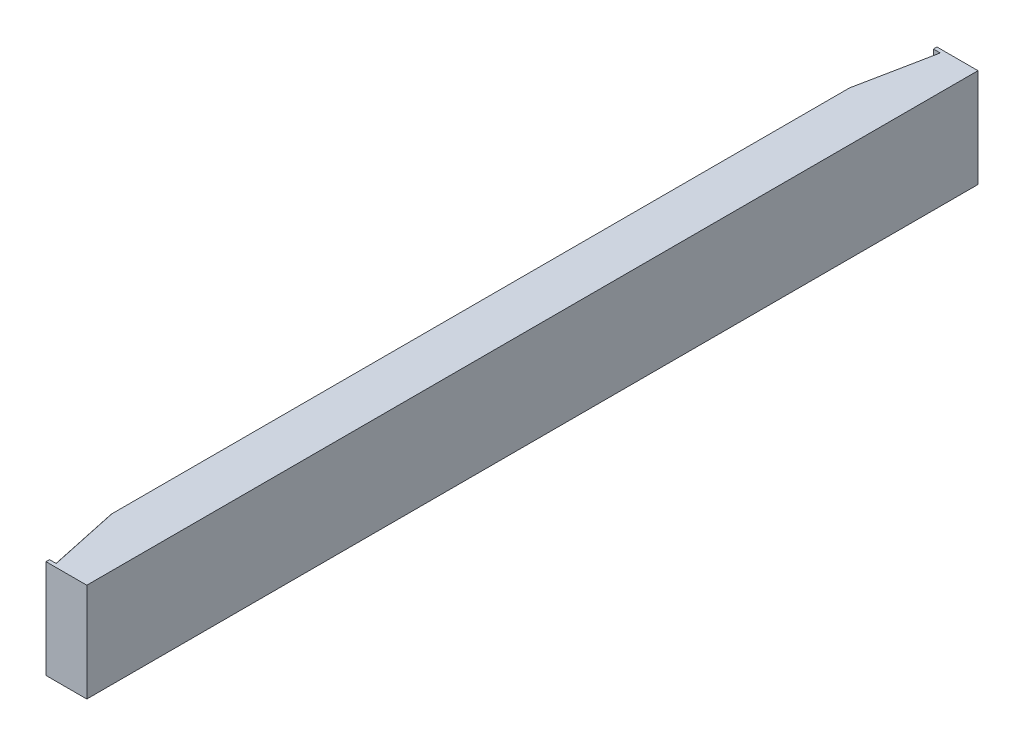
SolidWorks part; units mm, degrees
ref_plane "Front Plane" through (0, 0, 0) normal (0, 0, 1) x (1, 0, 0)
ref_plane "Top Plane" through (0, 0, 0) normal (0, 1, 0) x (1, 0, 0)
ref_plane "Right Plane" through (0, 0, 0) normal (1, 0, 0) x (0, 0, -1)
sketch "Sketch1" plane through (0, 0, 0) normal (0, 0, 1) x (1, 0, 0)
  line L1 (300, 147.1759) -> (450, 147.1759)
  line L2 (300, 147.1759) -> (300, -152.8241)
  line L3 (300, -152.8241) -> (450, -152.8241)
  line L4 (450, 147.1759) -> (450, -152.8241)
  line L5 (0, 0) -> (300, -2.8241) construction
  line L14 (0, 275) -> (0, -275)
  line L15 (0, -275) -> (300, -275)
  line L16 (300, -275) -> (300, 275)
  line L17 (300, 275) -> (0, 275)
  dimension "D2" = 300
  dimension "D3" = 150
extrude "Boss-Extrude1" add sketch "Sketch1" along normal blind 500 and the other way blind 1600 contours L4 L1 L2 L16 L3
sketch "Sketch2" plane through (0, 0, -1600) normal (0, 0, -1) x (-1, 0, 0)
  line L22 (-300, 49.6759) -> (-300, 69.6759)
  line L23 (-300, 69.6759) -> (-325, 69.6759)
  line L24 (-325, 69.6759) -> (-325, 77.1759)
  line L25 (-300, 129.6759) -> (-325, 129.6759)
  line L26 (-300, 147.1759) -> (-300, -152.8241) construction
  line L27 (-325, 129.6759) -> (-325, 137.1759)
  line L28 (-325, 137.1759) -> (-345, 137.1759)
  line L29 (-345, 137.1759) -> (-345, 102.1759)
  line L30 (-345, 102.1759) -> (-325, 102.1759)
  line L31 (-325, 102.1759) -> (-325, 109.6759)
  line L32 (-325, 109.6759) -> (-300, 109.6759)
  line L33 (-300, 109.6759) -> (-300, 129.6759)
  line L66 (-300, 147.1759) -> (-450, 147.1759) construction
  line L67 (-300, 119.6759) -> (-390, 119.6759) construction
  line L68 (-325, 77.1759) -> (-345, 77.1759)
  line L69 (-345, 77.1759) -> (-345, 42.1759)
  line L70 (-345, 42.1759) -> (-325, 42.1759)
  line L71 (-325, 42.1759) -> (-325, 49.6759)
  line L72 (-325, 49.6759) -> (-300, 49.6759)
  line L73 (-300, -10.3241) -> (-300, 9.6759)
  line L74 (-300, 9.6759) -> (-325, 9.6759)
  line L75 (-325, 9.6759) -> (-325, 17.1759)
  line L76 (-325, 17.1759) -> (-345, 17.1759)
  line L77 (-345, 17.1759) -> (-345, -17.8241)
  line L78 (-345, -17.8241) -> (-325, -17.8241)
  line L79 (-325, -17.8241) -> (-325, -10.3241)
  line L80 (-325, -10.3241) -> (-300, -10.3241)
  line L81 (-300, -70.3241) -> (-300, -50.3241)
  line L82 (-300, -50.3241) -> (-325, -50.3241)
  line L83 (-325, -50.3241) -> (-325, -42.8241)
  line L84 (-325, -42.8241) -> (-345, -42.8241)
  line L85 (-345, -42.8241) -> (-345, -77.8241)
  line L86 (-345, -77.8241) -> (-325, -77.8241)
  line L87 (-325, -77.8241) -> (-325, -70.3241)
  line L88 (-325, -70.3241) -> (-300, -70.3241)
  line L89 (-300, -130.3241) -> (-300, -110.3241)
  line L90 (-300, -110.3241) -> (-325, -110.3241)
  line L91 (-325, -110.3241) -> (-325, -102.8241)
  line L92 (-325, -102.8241) -> (-345, -102.8241)
  line L93 (-345, -102.8241) -> (-345, -137.8241)
  line L94 (-345, -137.8241) -> (-325, -137.8241)
  line L95 (-325, -137.8241) -> (-325, -130.3241)
  line L96 (-325, -130.3241) -> (-300, -130.3241)
  point P52 (-345, 119.6759)
  dimension "D1" = 5
  dimension "D2" = 20
  dimension "D4" = 45
  dimension "D5" = 25
  dimension "D3" = 10
  dimension "D6" = 20
  dimension "D7" = 35
extrude "Cut-Extrude1" cut sketch "Sketch2" against normal blind 2309
sketch "Sketch5" plane through (0, 0, 500) normal (0, 0, 1) x (1, 0, 0)
  line L1 (300, -152.8241) -> (450, -152.8241)
  line L2 (300, -152.8241) -> (300, 147.1759)
  line L3 (300, 147.1759) -> (450, 147.1759)
  line L4 (450, -152.8241) -> (450, 147.1759)
extrude "Boss-Extrude2" add sketch "Sketch5" along normal blind 350
sketch "Sketch6" plane through (300, 0, 0) normal (-1, 0, 0) x (0, 0, 1)
  line L0 (850, 147.1759) -> (850, -152.8241) construction
  line L1 (580, -127.8241) -> (790, -127.8241)
  line L2 (580, -127.8241) -> (580, 122.1759)
  line L3 (580, 122.1759) -> (790, 122.1759)
  line L4 (790, -127.8241) -> (790, 122.1759)
  line L6 (-1600, -152.8241) -> (850, -152.8241) construction
  line L7 (-1600, 147.1759) -> (850, 147.1759) construction
  dimension "D1" = 60
  dimension "D3" = 25
  dimension "D4" = 25
extrude "Cut-Extrude4" cut sketch "Sketch6" against normal blind 45
sketch "Sketch7" plane through (0, 122.1759, 0) normal (0, -1, 0) x (1, 0, 0)
  line L0 (300, 580) -> (345, 790)
  line L1 (345, 790) -> (300, 790)
  line L2 (300, 790) -> (300, 580)
extrude "Cut-Extrude5" cut sketch "Sketch7" against normal mid plane 3000
sketch "Sketch8" plane through (0, -152.8241, 0) normal (0, -1, 0) x (1, 0, 0)
  line L6 (450, 850) -> (450, 800.7476)
  line L7 (450, -1600) -> (450, 850) construction
  line L8 (450, 800.7476) -> (325, 800.7476)
  line L9 (325, 790) -> (300, 790)
  line L10 (345, 790) -> (300, 790) construction
  line L11 (300, 790) -> (300, 850)
  line L12 (300, 850) -> (450, 850)
  line L13 (325, 800.7476) -> (325, 790)
  dimension "D1" = 125
extrude "Cut-Extrude7" cut sketch "Sketch8" against normal blind 355
fillet "Fillet8" radius 1.5 4 edges at (325, 147.1759, 795.3738) (325, -2.8241, 800.7476) (325, -152.8241, 795.3738) (325, -2.8241, 790)
fillet "Fillet9" radius 1.5 4 edges at (322.5, -152.8241, 685) (322.5, -127.8241, 685) (322.5, 122.1759, 685) (322.5, 147.1759, 685)
sketch "Sketch9" plane through (0, 0, -1600) normal (0, 0, -1) x (-1, 0, 0)
  line L1 (-450, 147.1759) -> (-300, 147.1759)
  line L2 (-450, 147.1759) -> (-450, -152.8241)
  line L3 (-450, -152.8241) -> (-300, -152.8241)
  line L4 (-300, 147.1759) -> (-300, -152.8241)
extrude "Boss-Extrude3" add sketch "Sketch9" along normal blind 300
ref_plane "Plane1" through (0, -2.8241, 0) normal (0, -1, 0) x (-1, 0, 0)
sketch "Sketch10" plane through (0, -2.8241, 0) normal (0, -1, 0) x (-1, 0, 0)
  line L7 (-300, 1670) -> (-370, 1670)
  line L10 (-370, 1670) -> (-370, 1900)
  line L12 (-370, 1900) -> (-300, 1900)
  line L14 (-300, 1900) -> (-300, -572.8411) construction
  line L15 (-450, 1900) -> (-300, 1900) construction
  line L16 (-300, 1670) -> (-300, 1900)
  dimension "D1" = 230
  dimension "D2" = 70
extrude "Cut-Extrude17" cut sketch "Sketch10" against normal mid plane 280
sketch "Sketch11" plane through (0, -152.8241, 0) normal (0, -1, 0) x (1, 0, 0)
  line L1 (450, -1900) -> (325, -1900)
  line L2 (450, -1900) -> (450, -1910.75)
  line L3 (450, -1910.75) -> (325, -1910.75)
  line L4 (325, -1900) -> (325, -1910.75)
  dimension "D1" = 125
  dimension "D2" = 10.75
extrude "Boss-Extrude4" add sketch "Sketch11" against normal up to surface (300 mm away) up to face at (357.0763, 147.1759, -6.5234)
sketch "Sketch13" plane through (0, -152.8241, 0) normal (0, -1, 0) x (1, 0, 0)
  line L0 (300, -1900) -> (345.9801, -1900)
  line L1 (345.9801, -1900) -> (300, -1670)
  line L2 (300, -1900) -> (300, 572.8411) construction
  line L3 (300, -1670) -> (300, -1900)
  dimension "D1" = 230
extrude "Cut-Extrude18" cut sketch "Sketch13" against normal blind 394
ref_plane "Plane3" through (0, 0, -1449.2524) normal (0, 0, 1) x (1, 0, 0)
sketch "Sketch15" plane through (0, 0, -1449.2524) normal (0, 0, 1) x (1, 0, 0)
  line L0 (350, -145.9026) -> (350, -197.2648)
  line L1 (340, -207.2648) -> (304.1129, -207.2648)
  arc A0 (350, -197.2648) -> (340, -207.2648) centre (340, -197.2648) cw
  dimension "D1" = 10
sweep "Sweep1" add path "Sketch15" circular profile diameter 15 parameters "D3"=15
sketch "Sketch50" plane through (304.1129, 0, 0) normal (-1, 0, 0) x (0, 0, 1)
  circle A0 centre (-1449.2524, -207.2648) radius 4.3351
extrude "Boss-Extrude5" add sketch "Sketch50" along normal blind 20
sketch "Sketch82" plane through (0, -110.3241, 0) normal (0, -1, 0) x (1, 0, 0)
  line L0 (300, 500) -> (300, -1600) construction
  line L1 (300, -1560) -> (345, -1560)
  line L2 (300, -1560) -> (300, -1530)
  line L3 (300, -1530) -> (345, -1530)
  line L4 (345, -1560) -> (345, -1530)
  line L5 (300, -1600) -> (325, -1600) construction
  dimension "D1" = 45
  dimension "D2" = 30
  dimension "D3" = 40
extrude "Cut-Extrude19" cut sketch "Sketch82" against normal blind 250 and the other way blind 30
sketch "Sketch85" plane through (0, -110.3241, 0) normal (0, -1, 0) x (1, 0, 0)
  line L0 (300, 500) -> (300, -1530) construction
  line L1 (300, 430) -> (345, 430)
  line L2 (300, 430) -> (300, 460)
  line L3 (300, 460) -> (345, 460)
  line L4 (345, 430) -> (345, 460)
  line L5 (325, 500) -> (300, 500) construction
  dimension "D1" = 40
  dimension "D2" = 30
  dimension "D3" = 45
extrude "Cut-Extrude20" cut sketch "Sketch85" against normal blind 250 and the other way blind 32
